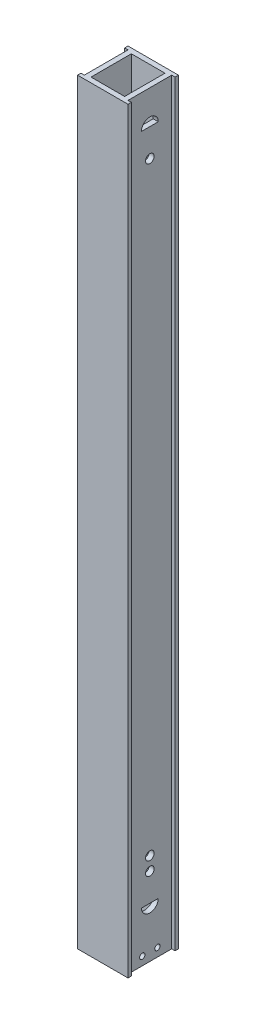
SolidWorks part; units mm, degrees
ref_plane "前视基准面" through (0, 0, 0) normal (0, 0, 1) x (1, 0, 0)
ref_plane "上视基准面" through (0, 0, 0) normal (0, 1, 0) x (1, 0, 0)
ref_plane "右视基准面" through (0, 0, 0) normal (1, 0, 0) x (0, 0, -1)
other "Configuration Table"
sketch "草图1" plane through (0, 0, 0) normal (0, 0, 1) x (1, 0, 0)
  line L0 (0, 0) -> (324.4923, 0) construction
  line L1 (0, 0) -> (0, 279.3401) construction
  line L2 (-15, 225) -> (15, 225)
  line L3 (-15, 225) -> (-15, -225)
  line L4 (-15, -225) -> (15, -225)
  line L5 (15, -225) -> (15, 225)
  point P6 (0, 225)
  point P10 (-15, 0)
  dimension "D1" = 450
  dimension "D2" = 30
extrude "凸台-拉伸1" add sketch "草图1" along normal blind 30
sketch "草图2" plane through (0, 225, 0) normal (0, 1, 0) x (1, 0, 0)
  line L0 (0, 0) -> (0, -20.1827) construction
  line L1 (0, -10) -> (15.4868, -10) construction
  line L2 (-15, -2) -> (-13, -2)
  line L3 (-13, -2) -> (-13, -28)
  line L4 (-13, -28) -> (-15, -28)
  line L5 (15, -30) -> (15, 0) construction
  line L6 (-15, -30) -> (-15, 0) construction
  line L7 (15, -28) -> (15, -2)
  line L8 (-15, -28) -> (-15, -2)
  line L9 (15, 0) -> (-15, 0) construction
  line L10 (15, -30) -> (-15, -30) construction
  line L11 (13, -28) -> (15, -28)
  line L12 (13, -2) -> (13, -28)
  line L13 (15, -2) -> (13, -2)
  dimension "D2" = 2
  dimension "D1" = 2
  dimension "D3" = 2
extrude "切除-拉伸1" cut sketch "草图2" against normal through all
shell "抽壳1" thickness 3
sketch "草图3" plane through (13, 0, 0) normal (1, 0, 0) x (0, 0, -1)
  line L0 (0, 0) -> (170.4874, 0) construction
  line L1 (-15, 225) -> (-15, -46.9872) construction
  line L2 (-20, 205) -> (-10, 205)
  line L3 (-2, 225) -> (-28, 225) construction
  line L4 (-20, -195) -> (-10, -195)
  line L5 (-2, -225) -> (-28, -225) construction
  line L6 (-30, -225) -> (-30, 225) construction
  arc A1 (-10, 205) -> (-20, 205) centre (-15, 205) ccw
  arc A2 (-10, -195) -> (-20, -195) centre (-15, -195) cw
  circle A3 centre (-15, 188.5) radius 2.55
  circle A4 centre (-15, -178.5) radius 2.55
  circle A5 centre (-19.5, -220) radius 1.6
  circle A6 centre (-15, -170.5) radius 2.55
  circle A7 centre (-10.5, -220) radius 1.6
  point P18 (-15, -225)
  point P25 (0, 0)
  dimension "D1" = 20
  dimension "D2" = 5
  dimension "D3" = 30
  dimension "D4" = 5
  dimension "D7" = 5.1
  dimension "D8" = 3.2
  dimension "D10" = 5.1
  dimension "D13" = 3.2
  dimension "D5" = 16.5
  dimension "D6" = 16.5
  dimension "D9" = 5
  dimension "D11" = 8
  dimension "D12" = 4.5
  dimension "D14" = 4.5
  dimension "D15" = 5
extrude "切除-拉伸2" cut sketch "草图3" against normal through all
